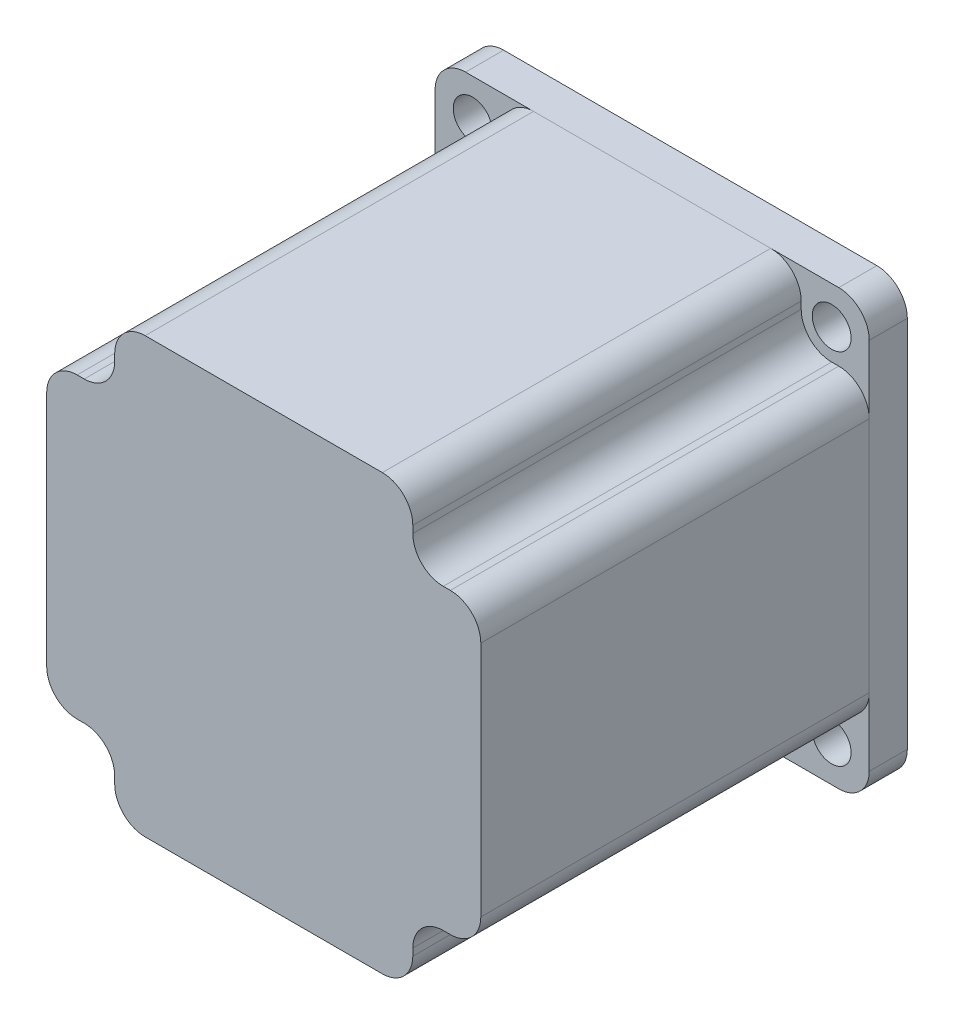
SolidWorks part; units mm, degrees
ref_plane "Front Plane" through (0, 0, 0) normal (0, 0, 1) x (1, 0, 0)
ref_plane "Top Plane" through (0, 0, 0) normal (0, 1, 0) x (1, 0, 0)
ref_plane "Right Plane" through (0, 0, 0) normal (1, 0, 0) x (0, 0, -1)
sketch "Sketch2" plane through (0, 0, 0) normal (0, 0, 1) x (1, 0, 0)
  line L11 (24.5, 28.5) -> (-24.5, 28.5)
  line L12 (-28.5, 24.5) -> (-28.5, 16.9563)
  line L13 (-28.5, 16.9563) -> (-28.5, 14.8688)
  line L14 (-28.5, 14.8688) -> (-28.5, 12.4439)
  line L15 (-28.5, 12.4439) -> (-28.5, 10.3563)
  line L16 (-28.5, 10.3563) -> (-28.5, -10.3563)
  line L17 (-28.5, -10.3563) -> (-28.5, -12.4439)
  line L18 (-28.5, -12.4439) -> (-28.5, -14.8688)
  line L19 (-28.5, -14.8688) -> (-28.5, -16.9563)
  line L20 (-28.5, -16.9563) -> (-28.5, -24.5)
  line L21 (-24.5, -28.5) -> (24.5, -28.5)
  line L27 (28.5, -10.3563) -> (28.5, 10.3563)
  line L28 (28.5, 16.9563) -> (28.5, 24.5)
  line L29 (28.5, 14.8688) -> (28.5, 16.9563)
  line L30 (28.5, 12.4439) -> (28.5, 14.8688)
  line L31 (28.5, 10.3563) -> (28.5, 12.4439)
  line L36 (28.5, -24.5) -> (28.5, -16.9563)
  line L37 (28.5, -16.9563) -> (28.5, -14.8688)
  line L38 (28.5, -14.8688) -> (28.5, -12.4439)
  line L39 (28.5, -12.4439) -> (28.5, -10.3563)
  arc A2 (-24.5, 28.5) -> (-28.5, 24.5) centre (-24.5, 24.5) ccw
  arc A3 (-28.5, -24.5) -> (-24.5, -28.5) centre (-24.5, -24.5) ccw
  arc A5 (28.5, 24.5) -> (24.5, 28.5) centre (24.5, 24.5) ccw
  arc A7 (24.5, -28.5) -> (28.5, -24.5) centre (24.5, -24.5) ccw
  arc A16 (26.12, -23.57) -> (21.02, -23.57) centre (23.57, -23.57) ccw
  arc A17 (21.02, -23.57) -> (26.12, -23.57) centre (23.57, -23.57) ccw
  arc A18 (26.12, 23.57) -> (21.02, 23.57) centre (23.57, 23.57) ccw
  arc A19 (21.02, 23.57) -> (26.12, 23.57) centre (23.57, 23.57) ccw
  arc A20 (-21.02, 23.57) -> (-26.12, 23.57) centre (-23.57, 23.57) ccw
  arc A21 (-26.12, 23.57) -> (-21.02, 23.57) centre (-23.57, 23.57) ccw
  arc A22 (-21.02, -23.57) -> (-26.12, -23.57) centre (-23.57, -23.57) ccw
  arc A23 (-26.12, -23.57) -> (-21.02, -23.57) centre (-23.57, -23.57) ccw
extrude "Boss-Extrude1" add sketch "Sketch2" against normal blind 5
sketch "Sketch3" plane through (0, 0, 0) normal (0, 0, 1) x (1, 0, 0)
  line L49 (-15.57, -28.5) -> (15.57, -28.5)
  line L50 (19.57, -24.5) -> (19.57, -23.57)
  line L51 (23.57, -19.57) -> (24.5, -19.57)
  line L52 (28.5, -15.57) -> (28.5, 15.57)
  line L53 (24.5, 19.57) -> (23.57, 19.57)
  line L54 (19.57, 23.57) -> (19.57, 24.5)
  line L55 (15.57, 28.5) -> (-15.57, 28.5)
  line L56 (-19.57, 24.5) -> (-19.57, 23.57)
  line L57 (-23.57, 19.57) -> (-24.5, 19.57)
  line L58 (-28.5, 15.57) -> (-28.5, -15.57)
  line L59 (-24.5, -19.57) -> (-23.57, -19.57)
  line L60 (-19.57, -23.57) -> (-19.57, -24.5)
  arc A60 (-19.57, -24.5) -> (-15.57, -28.5) centre (-15.57, -24.5) ccw
  arc A61 (15.57, -28.5) -> (19.57, -24.5) centre (15.57, -24.5) ccw
  arc A62 (23.57, -19.57) -> (19.57, -23.57) centre (23.57, -23.57) ccw
  arc A63 (24.5, -19.57) -> (28.5, -15.57) centre (24.5, -15.57) ccw
  arc A64 (28.5, 15.57) -> (24.5, 19.57) centre (24.5, 15.57) ccw
  arc A65 (19.57, 23.57) -> (23.57, 19.57) centre (23.57, 23.57) ccw
  arc A66 (19.57, 24.5) -> (15.57, 28.5) centre (15.57, 24.5) ccw
  arc A67 (-15.57, 28.5) -> (-19.57, 24.5) centre (-15.57, 24.5) ccw
  arc A68 (-23.57, 19.57) -> (-19.57, 23.57) centre (-23.57, 23.57) ccw
  arc A69 (-24.5, 19.57) -> (-28.5, 15.57) centre (-24.5, 15.57) ccw
  arc A70 (-28.5, -15.57) -> (-24.5, -19.57) centre (-24.5, -15.57) ccw
  arc A71 (-19.57, -23.57) -> (-23.57, -19.57) centre (-23.57, -23.57) ccw
extrude "Boss-Extrude2" add sketch "Sketch3" along normal blind 51 separate body
